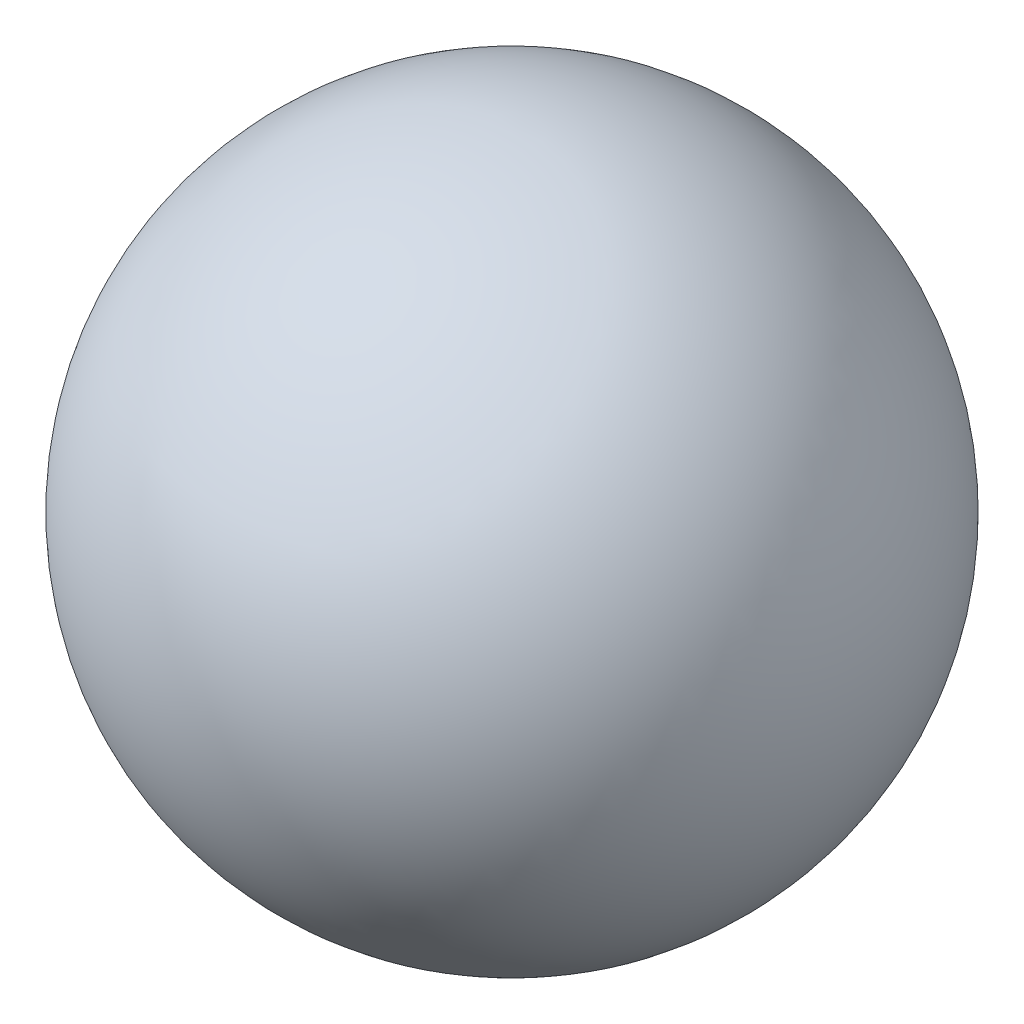
SolidWorks part; units mm, degrees
ref_plane "Front Plane" through (0, 0, 0) normal (0, 0, 1) x (1, 0, 0)
ref_plane "Top Plane" through (0, 0, 0) normal (0, 1, 0) x (1, 0, 0)
ref_plane "Right Plane" through (0, 0, 0) normal (1, 0, 0) x (0, 0, -1)
sketch "Sketch1" plane through (0, 0, 0) normal (1, 0, 0) x (0, 0, -1)
  line L0 (0, 34.29) -> (0, -34.29)
  circle A0 centre (0, 0) radius 34.29
  point P5 (0, 0)
  dimension "D1" = 68.58
revolve "Revolve1" add sketch "Sketch1" angle 360 about L0
